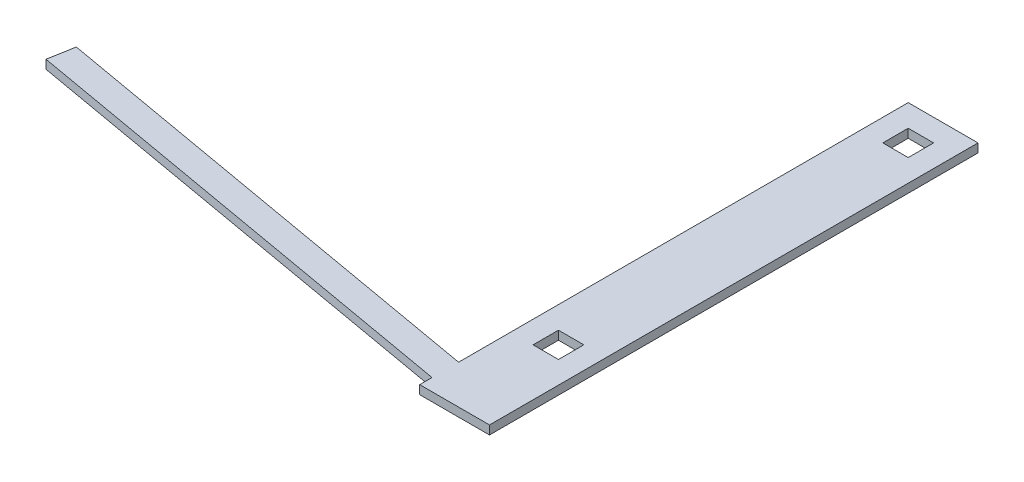
SolidWorks part; units mm, degrees
ref_plane "Front Plane" through (0, 0, 0) normal (0, 0, 1) x (1, 0, 0)
ref_plane "Top Plane" through (0, 0, 0) normal (0, 1, 0) x (1, 0, 0)
ref_plane "Right Plane" through (0, 0, 0) normal (1, 0, 0) x (0, 0, -1)
sketch "Sketch1" plane through (0, 0, 0) normal (0, 1, 0) x (1, 0, 0)
  line L1 (0.0081, 101.8928) -> (12.7081, 101.8928)
  line L2 (0.0081, 101.8928) -> (0.0081, 12.9928)
  line L3 (0.0081, 12.9928) -> (12.7081, 12.9928)
  line L4 (12.7081, 101.8928) -> (12.7081, 12.9928)
  line L6 (4.0481, 97.8528) -> (8.6681, 97.8528)
  line L7 (4.0481, 97.8528) -> (4.0481, 93.2328)
  line L8 (4.0481, 93.2328) -> (8.6681, 93.2328)
  line L9 (8.6681, 97.8528) -> (8.6681, 93.2328)
  line L27 (4.0481, 34.2028) -> (4.0481, 29.5828)
  line L28 (4.0481, 34.2028) -> (8.6681, 34.2028)
  line L29 (8.6681, 34.2028) -> (8.6681, 29.5828)
  line L30 (4.0481, 29.5828) -> (8.6681, 29.5828)
  line L31 (4.0481, 46.9328) -> (4.0481, 42.3128) [skipped]
  line L32 (4.0481, 42.3128) -> (8.6681, 42.3128) [skipped]
  line L33 (8.6681, 46.9328) -> (8.6681, 42.3128) [skipped]
  line L34 (4.0481, 46.9328) -> (8.6681, 46.9328) [skipped]
  line L35 (4.0481, 59.6628) -> (4.0481, 55.0428) [skipped]
  line L36 (4.0481, 55.0428) -> (8.6681, 55.0428) [skipped]
  line L37 (8.6681, 59.6628) -> (8.6681, 55.0428) [skipped]
  line L38 (4.0481, 59.6628) -> (8.6681, 59.6628) [skipped]
  line L39 (4.0481, 72.3928) -> (4.0481, 67.7728) [skipped]
  line L40 (4.0481, 67.7728) -> (8.6681, 67.7728) [skipped]
  line L41 (8.6681, 72.3928) -> (8.6681, 67.7728) [skipped]
  line L42 (4.0481, 72.3928) -> (8.6681, 72.3928) [skipped]
  line L43 (4.0481, 85.1228) -> (4.0481, 80.5028) [skipped]
  line L44 (4.0481, 80.5028) -> (8.6681, 80.5028) [skipped]
  line L45 (8.6681, 85.1228) -> (8.6681, 80.5028) [skipped]
  line L46 (4.0481, 85.1228) -> (8.6681, 85.1228) [skipped]
  dimension "D7" = 6
  dimension "D1" = 12.7
  dimension "D2" = 88.9
  dimension "D3" = 4.62
  dimension "D4" = 4.62
  dimension "D5" = 4.04
  dimension "D6" = 4.04
extrude "Boss-Extrude1" add sketch "Sketch1" along normal blind 1.5875
sketch "Sketch2" plane through (0, 0, 0) normal (0, -1, 0) x (1, 0, 0)
  line L0 (12.7081, -12.9928) -> (-85.2803, -30.2708)
  line L1 (-85.2803, -30.2708) -> (-84.4533, -34.9609)
  line L2 (-84.4533, -34.9609) -> (12.7081, -17.8288)
  line L3 (12.7081, -17.8288) -> (12.7081, -12.9928)
  line L4 (0.0081, -12.9928) -> (0.0081, -101.8928)
  line L5 (0.0081, -101.8928) -> (12.7081, -101.8928)
  line L6 (12.7081, -101.8928) -> (12.7081, -12.9928)
  line L7 (12.7081, -12.9928) -> (0.0081, -12.9928)
  line L8 (0.0081, -12.9928) -> (0.0081, -101.8928)
  line L9 (0.0081, -101.8928) -> (12.7081, -101.8928)
  line L10 (12.7081, -101.8928) -> (12.7081, -12.9928)
  line L11 (12.7081, -12.9928) -> (0.0081, -12.9928)
  line M6 (0.0081, -12.9928) -> (0.0081, -101.8928)
  dimension "D2" = 99.5
  dimension "D3" = 4.7625
  dimension "D4" = 80
  dimension "D1" = 0
extrude "Boss-Extrude2" add sketch "Sketch2" against normal up to surface (1.5875 mm away) contours L1 L2 L0 M6 up to face at (6.3581, 1.5875, -57.4428)
